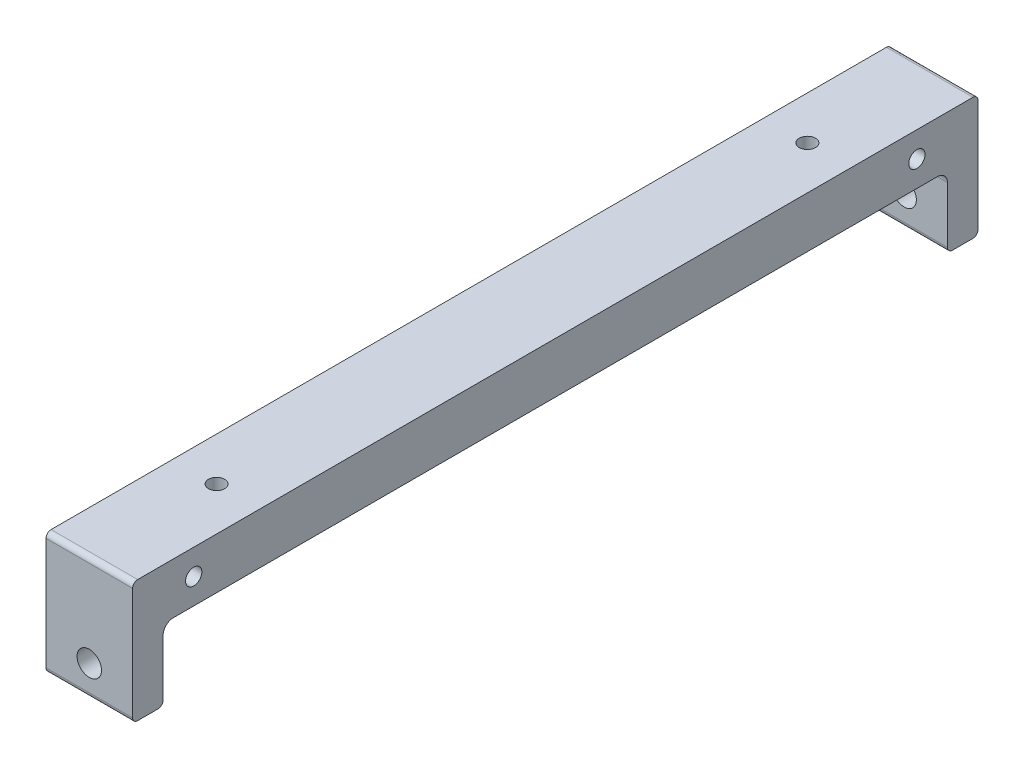
SolidWorks part; units mm, degrees
material "6061 Alloy"
ref_plane "Frontal" through (0, 0, 0) normal (0, 0, 1) x (1, 0, 0)
ref_plane "Superior" through (0, 0, 0) normal (0, 1, 0) x (1, 0, 0)
ref_plane "Direito" through (0, 0, 0) normal (1, 0, 0) x (0, 0, -1)
sketch "Sketch1" plane through (0, 0, 0) normal (0, 0, 1) x (1, 0, 0)
  line L1 (-4.25, -6) -> (4.25, -6)
  line L2 (-4.25, -6) -> (-4.25, 6)
  line L3 (-4.25, 6) -> (4.25, 6)
  line L4 (4.25, -6) -> (4.25, 6)
  line L5 (-4.25, -6) -> (4.25, 6) construction
  line L6 (-4.25, 6) -> (4.25, -6) construction
  point P0 (0, 0)
  dimension "D1" = 8.5
  dimension "D2" = 12
extrude "Boss-Extrude1" add sketch "Sketch1" along normal mid plane 83
sketch "Sketch2" plane through (4.25, 0, 0) normal (1, 0, 0) x (0, 0, -1)
  line L0 (-37.5, 1) -> (37.5, 1)
  line L1 (38.5, 0) -> (38.5, -6)
  line L2 (-41.5, -6) -> (41.5, -6) construction
  line L3 (38.5, -6) -> (-38.5, -6)
  line L4 (-38.5, -6) -> (-38.5, 0)
  line L5 (-41.5, 6) -> (41.5, 6) construction
  line L6 (-41.5, -6) -> (-41.5, 6) construction
  line L7 (41.5, -6) -> (41.5, 6) construction
  arc A0 (-37.5, 1) -> (-38.5, 0) centre (-37.5, 0) ccw
  arc A1 (37.5, 1) -> (38.5, 0) centre (37.5, 0) cw
  dimension "D4" = 1
  dimension "D5" = 1
  dimension "D1" = 5
  dimension "D2" = 3
  dimension "D3" = 3
extrude "Cut-Extrude1" cut sketch "Sketch2" against normal through all
fillet "Fillet1" radius 0.5 6 edges at (0, 6, -41.5) (0, 6, 41.5) (0, -6, -41.5) (0, -6, -38.5) (0, -6, 38.5) (0, -6, 41.5)
hole_wizard "M2 Hole1-J" positions "Sketch10" profile "Sketch9" hole size "M2" standard "DIN"
sketch "Sketch10" plane through (4.25, 0, 0) normal (1, 0, 0) x (0, 0, -1)
  line L0 (-41, 6) -> (41, 6) construction
  line L1 (-41.5, -5.5) -> (-41.5, 5.5) construction
  line L2 (41.5, -5.5) -> (41.5, 5.5) construction
  point P0 (-35.5, 3.5)
  point P2 (35.5, 3.5)
  dimension "D1" = 2.5
  dimension "D2" = 6
  dimension "D3" = 6
sketch "Sketch9" plane through (4.25, 3.5, 35.5) normal (0, 1, 0) x (0, 0, -1)
  line L0 (0, 0) -> (0, 5.4807)
  line L1 (0, 5.4807) -> (0.8, 5)
  line L2 (0.8, 5) -> (0.8, 0)
  line L5 (0.8, 0) -> (0, 0)
  line L10 (0, 5.4807) -> (-0.8, 5) construction
  line L11 (0, -6.35) -> (0, 107.95) construction
  dimension "Hole Dia." = 1.6
  dimension "Hole Depth" = 5
  dimension "Drill Angle" = 118
hole_wizard "M2 Hole2-K" positions "Sketch19" profile "Sketch18" hole size "M2" standard "DIN"
sketch "Sketch19" plane through (-4.25, 0, 0) normal (-1, 0, 0) x (0, 0, 1)
  line L0 (-41.5, 5.5) -> (-41.5, -5.5) construction
  line L1 (41.5, 5.5) -> (41.5, -5.5) construction
  line L2 (41, 6) -> (-41, 6) construction
  point P0 (-21.5, 3.5)
  point P2 (21.5, 3.5)
  dimension "D1" = 20
  dimension "D2" = 20
  dimension "D3" = 2.5
sketch "Sketch18" plane through (-4.25, 3.5, -21.5) normal (0, 1, 0) x (0, 0, 1)
  line L0 (0, 0) -> (0, 5.4807)
  line L1 (0, 5.4807) -> (0.8, 5)
  line L2 (0.8, 5) -> (0.8, 0)
  line L5 (0.8, 0) -> (0, 0)
  line L10 (0, 5.4807) -> (-0.8, 5) construction
  line L11 (0, -6.35) -> (0, 107.95) construction
  dimension "Hole Dia." = 1.6
  dimension "Hole Depth" = 5
  dimension "Drill Angle" = 118
hole_wizard "M2 Hole3-L" positions "Sketch8" profile "Sketch7" hole size "M2" standard "DIN"
sketch "Sketch8" plane through (0, 0, 41.5) normal (0, 0, 1) x (1, 0, 0)
  line L0 (4.25, -6) -> (-4.25, -6) construction
  point P0 (0, -3)
  dimension "D1" = 3
sketch "Sketch7" plane through (0, -3, 41.5) normal (1, 0, 0) x (0, -1, 0)
  line L0 (0, 0) -> (0, 10.721)
  line L1 (0, 10.721) -> (1.2, 10)
  line L2 (1.2, 10) -> (1.2, 0)
  line L5 (1.2, 0) -> (0, 0)
  line L10 (0, 10.721) -> (-1.2, 10) construction
  line L11 (0, -6.35) -> (0, 107.95) construction
  dimension "Hole Dia." = 2.4
  dimension "Hole Depth" = 10
  dimension "Drill Angle" = 118
hole_wizard "M2 Hole4-M" positions "Sketch15" profile "Sketch14" hole size "M2" standard "DIN" end condition through all
sketch "Sketch15" plane through (0, 6, 0) normal (0, 1, 0) x (1, 0, 0)
  line L0 (-4.25, -41) -> (-4.25, 41) construction
  line L1 (-4.25, 41.5) -> (4.25, 41.5) construction
  line L2 (4.25, -41.5) -> (-4.25, -41.5) construction
  point P0 (0, 29)
  point P2 (0, -29)
  dimension "D1" = 4.25
  dimension "D2" = 12.5
  dimension "D3" = 12.5
sketch "Sketch14" plane through (0, 6, -29) normal (1, 0, 0) x (0, 0, 1)
  line L0 (0, 0) -> (0, 12)
  line L1 (0, 12) -> (0.8, 12)
  line L2 (0.8, 12) -> (0.8, 0)
  line L5 (0.8, 0) -> (0, 0)
  line L11 (0, -6.35) -> (0, 107.95) construction
  dimension "Thru Hole Dia." = 1.6
  dimension "Thru Hole Depth" = 12
hole_wizard "M2 Hole5-N" positions "Sketch12" profile "Sketch11" hole size "M2" standard "DIN"
sketch "Sketch12" plane through (-4.25, 0, 0) normal (-1, 0, 0) x (0, 0, 1)
  line L0 (41, 6) -> (-41, 6) construction
  point P0 (0, 3.5)
  dimension "D1" = 2.5
sketch "Sketch11" plane through (-4.25, 3.5, 0) normal (0, 1, 0) x (0, 0, 1)
  line L0 (0, 0) -> (0, 4.4807)
  line L1 (0, 4.4807) -> (0.8, 4)
  line L2 (0.8, 4) -> (0.8, 0)
  line L5 (0.8, 0) -> (0, 0)
  line L10 (0, 4.4807) -> (-0.8, 4) construction
  line L11 (0, -6.35) -> (0, 107.95) construction
  dimension "Hole Dia." = 1.6
  dimension "Hole Depth" = 4
  dimension "Drill Angle" = 118
hole_wizard "M2 Hole6-P" positions "Sketch17" profile "Sketch16" hole size "M2" standard "DIN"
sketch "Sketch17" plane through (0, 0, -41.5) normal (0, 0, -1) x (-1, 0, 0)
  line L0 (4.25, 5.5) -> (4.25, -5.5) construction
  line L1 (-4.25, 6) -> (4.25, 6) construction
  point P0 (0, -3)
  dimension "D1" = 4.25
  dimension "D2" = 9
sketch "Sketch16" plane through (0, -3, -41.5) normal (1, 0, 0) x (0, 1, 0)
  line L0 (0, 0) -> (0, 10.721)
  line L1 (0, 10.721) -> (1.2, 10)
  line L2 (1.2, 10) -> (1.2, 0)
  line L5 (1.2, 0) -> (0, 0)
  line L10 (0, 10.721) -> (-1.2, 10) construction
  line L11 (0, -6.35) -> (0, 107.95) construction
  dimension "Hole Dia." = 2.4
  dimension "Hole Depth" = 10
  dimension "Drill Angle" = 118
